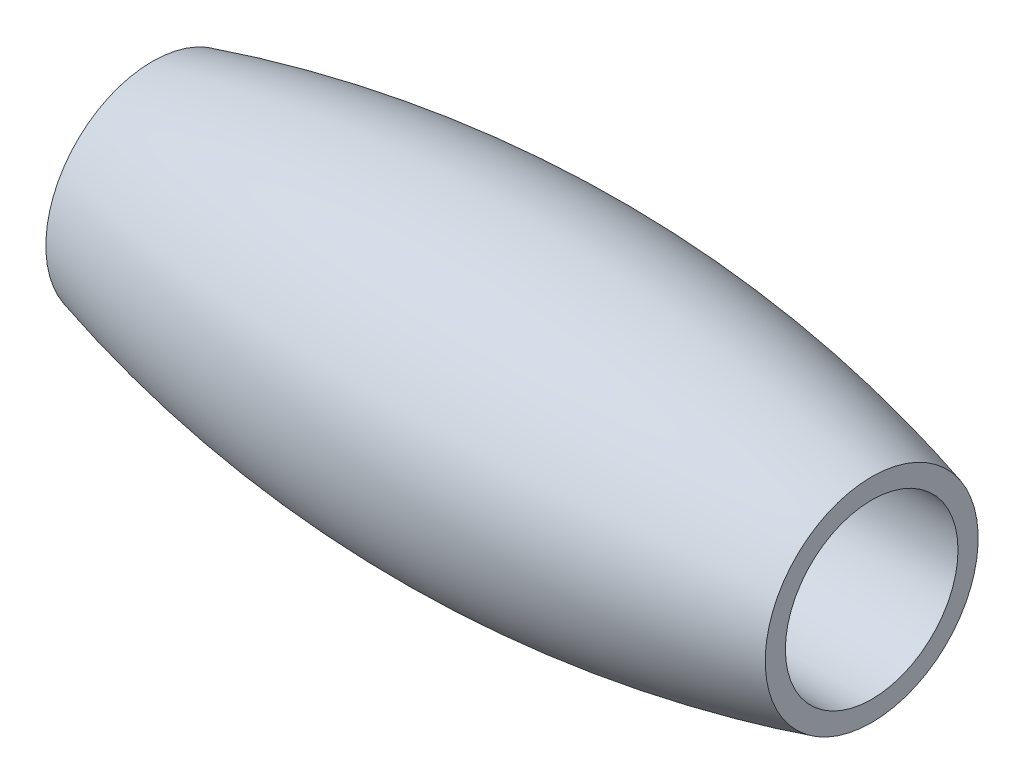
SolidWorks part; units mm, degrees
ref_plane "Front Plane" through (0, 0, 0) normal (0, 0, 1) x (1, 0, 0)
ref_plane "Top Plane" through (0, 0, 0) normal (0, 1, 0) x (1, 0, 0)
ref_plane "Right Plane" through (0, 0, 0) normal (1, 0, 0) x (0, 0, -1)
ref_plane "Plane1" through (0, 0, 0) normal (0, 0, -1) x (-1, 0, 0)
sketch "Sketch1" plane through (0, 0, 0) normal (0, 0, -1) x (-1, 0, 0)
  line L0 (-18.75, 5.55) -> (-18.75, 4.5)
  line L1 (-18.75, 4.5) -> (18.75, 4.5)
  line L2 (18.75, 4.5) -> (18.75, 5.55)
  line L3 (-18.75, 0) -> (18.75, 0) construction
  arc A0 (18.75, 5.55) -> (-18.75, 5.55) centre (0, -62.1088) ccw
  point P7 (0, 0)
  point P8 (19.9482, 2.9943)
  point P9 (0, 0)
  point P10 (0, 0)
  point P11 (19.6631, 2.5281)
  point P13 (19.6631, 2.5281)
  point P14 (0, 0)
  point P15 (0, 0)
  point P16 (0, 0)
  point P17 (0, 0)
  point P18 (0, 0)
  dimension "D1" = 37.5
  dimension "D2" = 70.2088
  dimension "D4" = 8.1
  dimension "D3" = 4.5
revolve "Revolve1" add sketch "Sketch1" angle 360 about L3
